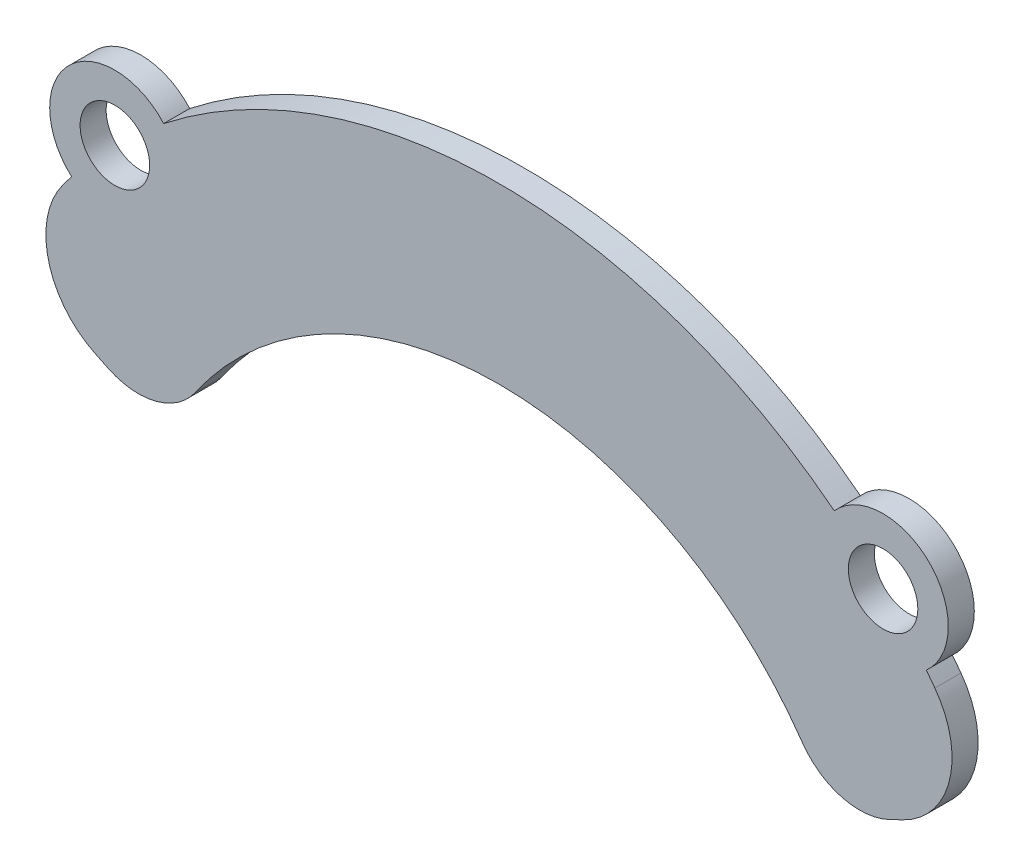
SolidWorks part; units mm, degrees
material "Galvanized Steel"
ref_plane "Front Plane" through (0, 0, 0) normal (0, 0, 1) x (1, 0, 0)
ref_plane "Top Plane" through (0, 0, 0) normal (0, 1, 0) x (1, 0, 0)
ref_plane "Right Plane" through (0, 0, 0) normal (1, 0, 0) x (0, 0, -1)
sketch "Sketch1" plane through (0, 0, 0) normal (0, 0, 1) x (1, 0, 0)
  line L0 (-1.8614, 0) -> (142.7999, 0)
  line L1 (0, 0) -> (44.1942, 44.1942)
  line L2 (0, 0) -> (0, 71.7772)
  line L3 (46.4598, 22.3101) -> (44.9485, 21.5843)
  line L4 (-46.4598, 22.3101) -> (-44.9485, 21.5843)
  arc A0 (34.9135, 24.2342) -> (-34.9135, 24.2342) centre (0, 0) ccw
  arc A1 (50.156, 37.2912) -> (-50.156, 37.2912) centre (0, 0) ccw
  arc A2 (49.1697, 38.5822) -> (38.5822, 49.1697) centre (44.1942, 44.1942) ccw
  arc A3 (-49.1697, 38.5822) -> (-38.5822, 49.1697) centre (-44.1942, 44.1942) cw
  arc A4 (-34.9135, 24.2342) -> (-44.9485, 21.5843) centre (-41.4855, 28.7959) cw
  arc A5 (34.9135, 24.2342) -> (44.9485, 21.5843) centre (41.4855, 28.7959) ccw
  arc A6 (-50.156, 37.2912) -> (-46.4598, 22.3101) centre (-42.131, 31.3246) ccw
  arc A7 (50.156, 37.2912) -> (46.4598, 22.3101) centre (42.131, 31.3246) cw
  point P15 (-38.3117, 18.3973)
  point P18 (38.3117, 18.3973)
  point P21 (-56.3408, 27.0549)
  point P24 (56.3408, 27.0549)
  dimension "D1" = 85
  dimension "D2" = 125
  dimension "D4" = 15
  dimension "D5" = 8
  dimension "D6" = 10
  dimension "D3" = 45
extrude "Boss-Extrude1" add sketch "Sketch1" along normal blind 3 contours A1 A6 L4 A4 A0 L2 | L1 A1 L2 A0 | A7 A1 L1 A0 A5 L3 | A1 A2 | A3 A1
sketch "Sketch2" plane through (0, 0, 3) normal (0, 0, 1) x (1, 0, 0)
  circle A0 centre (-44.1942, 44.1942) radius 4
  circle A1 centre (44.1942, 44.1942) radius 4
  dimension "D1" = 8
  dimension "D2" = 8
extrude "Cut-Extrude1" cut sketch "Sketch2" against normal blind 3
scale "Scale1" scale about centroid uniform scaling yes scale factor 3
